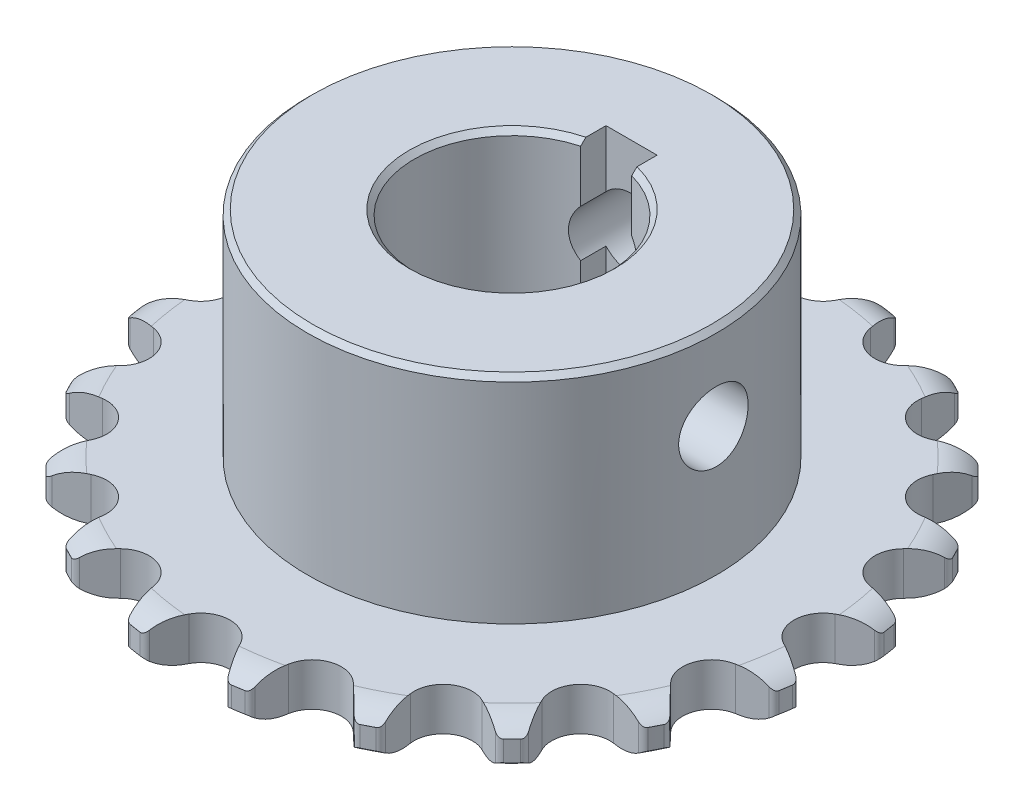
SolidWorks part; units mm, degrees
ref_plane "Alzado" through (0, 0, 0) normal (0, 0, 1) x (1, 0, 0)
ref_plane "Planta" through (0, 0, 0) normal (0, 1, 0) x (1, 0, 0)
ref_plane "Vista lateral" through (0, 0, 0) normal (1, 0, 0) x (0, 0, -1)
sketch "Croquis1" plane through (0, 0, 0) normal (0, 1, 0) x (1, 0, 0)
  circle A0 centre (0, 0) radius 9.55
  circle A1 centre (0, 0) radius 20
  dimension "D1" = 40
  dimension "D2" = 19.1
extrude "Saliente-Extruir1" add sketch "Croquis1" along normal blind 25.2
sketch "Croquis2" plane through (0, 25.2, 0) normal (0, 1, 0) x (1, 0, 0)
  line L0 (0, 11.7) -> (0, 20) construction
  line L1 (-2.5, 11.7) -> (2.5, 11.7)
  line L2 (-2.5, 11.7) -> (-2.5, 0)
  line L3 (-2.5, 0) -> (2.5, 0)
  line L4 (2.5, 11.7) -> (2.5, 0)
  circle A1 centre (0, 0) radius 20 construction
  point P4 (0, 11.7)
  point P13 (0, 0)
  dimension "D1" = 8.3
  dimension "D2" = 5
extrude "Cortar-Extruir1" cut sketch "Croquis2" against normal through all
sketch "Croquis4" plane through (0, 0, 0) normal (0, 0, 1) x (1, 0, 0)
  line L0 (0, 17.3) -> (0, 20.7) construction
  line L2 (9.55, 25.2) -> (-9.55, 25.2) construction
  circle A0 centre (0, 17.3) radius 3.4
  dimension "D2" = 6.8
  dimension "D1" = 4.5
extrude "Cortar-Extruir2" cut sketch "Croquis4" against normal through all
sketch "Croquis5" plane through (0, 0, 0) normal (1, 0, 0) x (0, 0, -1)
  line L0 (0, 16.8) -> (0, 20.2) construction
  line L2 (20, 25.2) -> (-20, 25.2) construction
  circle A0 centre (0, 16.8) radius 3.4
  dimension "D2" = 6.8
  dimension "D1" = 5
extrude "Cortar-Extruir3" cut sketch "Croquis5" along normal through all
sketch "Croquis6" plane through (0, 0, 0) normal (0, -1, 0) x (1, 0, 0)
  circle A0 centre (0, 0) radius 32.25
  circle A2 centre (0, 0) radius 20 construction
  circle A4 centre (0, 0) radius 18
  dimension "D1" = 64.5
  dimension "D2" = 2
extrude "Saliente-Extruir2" add sketch "Croquis6" against normal blind 4.2
sketch "Croquis11" plane through (0, 4.2, 0) normal (0, 1, 0) x (1, 0, 0)
  line L0 (0, 30.45) -> (0, 27.6) construction
  line L1 (2.5, 11.7) -> (-2.5, 11.7) construction
  circle A0 centre (0, 30.45) radius 2.85
  circle A1 centre (9.4096, 28.9597) radius 2.85
  circle A2 centre (17.8981, 24.6346) radius 2.85
  circle A3 centre (24.6346, 17.8981) radius 2.85
  circle A4 centre (28.9597, 9.4096) radius 2.85
  circle A5 centre (30.45, 0) radius 2.85
  circle A6 centre (28.9597, -9.4096) radius 2.85
  circle A7 centre (24.6346, -17.8981) radius 2.85
  circle A8 centre (17.8981, -24.6346) radius 2.85
  circle A9 centre (9.4096, -28.9597) radius 2.85
  circle A10 centre (0, -30.45) radius 2.85
  circle A11 centre (-9.4096, -28.9597) radius 2.85
  circle A12 centre (-17.8981, -24.6346) radius 2.85
  circle A13 centre (-24.6346, -17.8981) radius 2.85
  circle A14 centre (-28.9597, -9.4096) radius 2.85
  circle A15 centre (-30.45, 0) radius 2.85
  circle A16 centre (-28.9597, 9.4096) radius 2.85
  circle A17 centre (-24.6346, 17.8981) radius 2.85
  circle A18 centre (-17.8981, 24.6346) radius 2.85
  circle A19 centre (-9.4096, 28.9597) radius 2.85
  circle A20 centre (0, 0) radius 20 construction
  dimension "D1" = 5.7
  dimension "D2" = 15.9
  dimension "D4" = 9.4096
  dimension "D5" = 17.8981
  dimension "D6" = 24.6346
  dimension "D7" = 28.9597
  dimension "D8" = 30.45
  dimension "D9" = 17.8981
  dimension "D10" = 24.6346
  dimension "D11" = 28.9597
  dimension "D12" = 30.45
  dimension "D13" = 9.4096
  dimension "D3" = 9.4096
  dimension "D14" = 17.8981
  dimension "D15" = 24.6346
  dimension "D16" = 28.9597
  dimension "D17" = 9.4096
  dimension "D18" = 17.8981
  dimension "D19" = 24.6346
  dimension "D20" = 28.9597
  dimension "D21" = 30.45
  dimension "D22" = 30.45
  dimension "D23" = 30.45
  dimension "D24" = 30.45
extrude "Cortar-Extruir9" cut sketch "Croquis11" against normal through all
sketch "Croquis12" plane through (0, 4.2, 0) normal (0, 1, 0) x (1, 0, 0)
  line L0 (2.5142, 29.1078) -> (4.055, 31.9941)
  line L1 (6.0304, 31.6812) -> (6.6037, 28.4603)
  line L2 (2.2726, 32.1698) -> (3.555, 32.8941)
  line L3 (3.555, 32.8941) -> (4.055, 31.9941)
  line L4 (6.0304, 31.6812) -> (6.5304, 32.4295)
  line L5 (6.5304, 32.4295) -> (7.7797, 31.2976)
  line L6 (11.3859, 26.9062) -> (13.7433, 29.1751)
  line L7 (13.5458, 30.1855) -> (13.7433, 29.1751)
  line L8 (12.1024, 29.8931) -> (13.5458, 30.1855)
  line L9 (15.5253, 28.2671) -> (15.0752, 25.0267)
  line L10 (16.232, 28.8243) -> (17.0704, 27.3617)
  line L11 (15.5253, 28.2671) -> (16.232, 28.8243)
  line L12 (19.1431, 22.0709) -> (22.0862, 23.5003)
  line L13 (22.2107, 24.5223) -> (22.0862, 23.5003)
  line L14 (20.7475, 24.6901) -> (22.2107, 24.5223)
  line L15 (23.5004, 22.086) -> (22.071, 19.1433)
  line L16 (24.3448, 22.3976) -> (24.6901, 20.7475)
  line L17 (23.5004, 22.086) -> (24.3448, 22.3976)
  line L18 (25.0265, 15.0751) -> (28.2672, 15.5251)
  line L19 (28.7014, 16.4586) -> (28.2672, 15.5251)
  line L20 (27.3617, 17.0704) -> (28.7014, 16.4586)
  line L21 (29.1752, 13.743) -> (26.9064, 11.386)
  line L22 (30.0745, 13.7784) -> (29.8931, 12.1024)
  line L23 (29.1752, 13.743) -> (30.0745, 13.7784)
  line L24 (28.4601, 6.6037) -> (31.6812, 6.0302)
  line L25 (32.3827, 6.7838) -> (31.6812, 6.0302)
  line L26 (31.2976, 7.7797) -> (32.3827, 6.7838)
  line L27 (31.9941, 4.0548) -> (29.108, 2.5142)
  line L28 (32.8603, 3.8105) -> (32.1698, 2.2726)
  line L29 (31.9941, 4.0548) -> (32.8603, 3.8105)
  line L30 (29.1078, -2.5142) -> (31.9941, -4.055)
  line L31 (32.8941, -3.555) -> (31.9941, -4.055)
  line L32 (32.1698, -2.2726) -> (32.8941, -3.555)
  line L33 (31.6812, -6.0304) -> (28.4603, -6.6037)
  line L34 (32.4295, -6.5304) -> (31.2976, -7.7797)
  line L35 (31.6812, -6.0304) -> (32.4295, -6.5304)
  line L36 (26.9062, -11.3859) -> (29.1751, -13.7433)
  line L37 (30.1855, -13.5458) -> (29.1751, -13.7433)
  line L38 (29.8931, -12.1024) -> (30.1855, -13.5458)
  line L39 (28.2671, -15.5253) -> (25.0267, -15.0752)
  line L40 (28.8243, -16.232) -> (27.3617, -17.0704)
  line L41 (28.2671, -15.5253) -> (28.8243, -16.232)
  line L42 (22.0709, -19.1431) -> (23.5003, -22.0862)
  line L43 (24.5223, -22.2107) -> (23.5003, -22.0862)
  line L44 (24.6901, -20.7475) -> (24.5223, -22.2107)
  line L45 (22.086, -23.5004) -> (19.1433, -22.071)
  line L46 (22.3976, -24.3448) -> (20.7475, -24.6901)
  line L47 (22.086, -23.5004) -> (22.3976, -24.3448)
  line L48 (15.0751, -25.0265) -> (15.5251, -28.2672)
  line L49 (16.4586, -28.7014) -> (15.5251, -28.2672)
  line L50 (17.0704, -27.3617) -> (16.4586, -28.7014)
  line L51 (13.743, -29.1752) -> (11.386, -26.9064)
  line L52 (13.7784, -30.0745) -> (12.1024, -29.8931)
  line L53 (13.743, -29.1752) -> (13.7784, -30.0745)
  line L54 (6.6037, -28.4601) -> (6.0302, -31.6812)
  line L55 (6.7838, -32.3827) -> (6.0302, -31.6812)
  line L56 (7.7797, -31.2976) -> (6.7838, -32.3827)
  line L57 (4.0548, -31.9941) -> (2.5142, -29.108)
  line L58 (3.8105, -32.8603) -> (2.2726, -32.1698)
  line L59 (4.0548, -31.9941) -> (3.8105, -32.8603)
  line L60 (-2.5142, -29.1078) -> (-4.055, -31.9941)
  line L61 (-3.555, -32.8941) -> (-4.055, -31.9941)
  line L62 (-2.2726, -32.1698) -> (-3.555, -32.8941)
  line L63 (-6.0304, -31.6812) -> (-6.6037, -28.4603)
  line L64 (-6.5304, -32.4295) -> (-7.7797, -31.2976)
  line L65 (-6.0304, -31.6812) -> (-6.5304, -32.4295)
  line L66 (-11.3859, -26.9062) -> (-13.7433, -29.1751)
  line L67 (-13.5458, -30.1855) -> (-13.7433, -29.1751)
  line L68 (-12.1024, -29.8931) -> (-13.5458, -30.1855)
  line L69 (-15.5253, -28.2671) -> (-15.0752, -25.0267)
  line L70 (-16.232, -28.8243) -> (-17.0704, -27.3617)
  line L71 (-15.5253, -28.2671) -> (-16.232, -28.8243)
  line L72 (-19.1431, -22.0709) -> (-22.0862, -23.5003)
  line L73 (-22.2107, -24.5223) -> (-22.0862, -23.5003)
  line L74 (-20.7475, -24.6901) -> (-22.2107, -24.5223)
  line L75 (-23.5004, -22.086) -> (-22.071, -19.1433)
  line L76 (-24.3448, -22.3976) -> (-24.6901, -20.7475)
  line L77 (-23.5004, -22.086) -> (-24.3448, -22.3976)
  line L78 (-25.0265, -15.0751) -> (-28.2672, -15.5251)
  line L79 (-28.7014, -16.4586) -> (-28.2672, -15.5251)
  line L80 (-27.3617, -17.0704) -> (-28.7014, -16.4586)
  line L81 (-29.1752, -13.743) -> (-26.9064, -11.386)
  line L82 (-30.0745, -13.7784) -> (-29.8931, -12.1024)
  line L83 (-29.1752, -13.743) -> (-30.0745, -13.7784)
  line L84 (-28.4601, -6.6037) -> (-31.6812, -6.0302)
  line L85 (-32.3827, -6.7838) -> (-31.6812, -6.0302)
  line L86 (-31.2976, -7.7797) -> (-32.3827, -6.7838)
  line L87 (-31.9941, -4.0548) -> (-29.108, -2.5142)
  line L88 (-32.8603, -3.8105) -> (-32.1698, -2.2726)
  line L89 (-31.9941, -4.0548) -> (-32.8603, -3.8105)
  line L90 (-29.1078, 2.5142) -> (-31.9941, 4.055)
  line L91 (-32.8941, 3.555) -> (-31.9941, 4.055)
  line L92 (-32.1698, 2.2726) -> (-32.8941, 3.555)
  line L93 (-31.6812, 6.0304) -> (-28.4603, 6.6037)
  line L94 (-32.4295, 6.5304) -> (-31.2976, 7.7797)
  line L95 (-31.6812, 6.0304) -> (-32.4295, 6.5304)
  line L96 (-26.9062, 11.3859) -> (-29.1751, 13.7433)
  line L97 (-30.1855, 13.5458) -> (-29.1751, 13.7433)
  line L98 (-29.8931, 12.1024) -> (-30.1855, 13.5458)
  line L99 (-28.2671, 15.5253) -> (-25.0267, 15.0752)
  line L100 (-28.8243, 16.232) -> (-27.3617, 17.0704)
  line L101 (-28.2671, 15.5253) -> (-28.8243, 16.232)
  line L102 (-22.0709, 19.1431) -> (-23.5003, 22.0862)
  line L103 (-24.5223, 22.2107) -> (-23.5003, 22.0862)
  line L104 (-24.6901, 20.7475) -> (-24.5223, 22.2107)
  line L105 (-22.086, 23.5004) -> (-19.1433, 22.071)
  line L106 (-22.3976, 24.3448) -> (-20.7475, 24.6901)
  line L107 (-22.086, 23.5004) -> (-22.3976, 24.3448)
  line L108 (-15.0751, 25.0265) -> (-15.5251, 28.2672)
  line L109 (-16.4586, 28.7014) -> (-15.5251, 28.2672)
  line L110 (-17.0704, 27.3617) -> (-16.4586, 28.7014)
  line L111 (-13.743, 29.1752) -> (-11.386, 26.9064)
  line L112 (-13.7784, 30.0745) -> (-12.1024, 29.8931)
  line L113 (-13.743, 29.1752) -> (-13.7784, 30.0745)
  line L114 (-6.6037, 28.4601) -> (-6.0302, 31.6812)
  line L115 (-6.7838, 32.3827) -> (-6.0302, 31.6812)
  line L116 (-7.7797, 31.2976) -> (-6.7838, 32.3827)
  line L117 (-4.0548, 31.9941) -> (-2.5142, 29.108)
  line L118 (-3.8105, 32.8603) -> (-2.2726, 32.1698)
  line L119 (-4.0548, 31.9941) -> (-3.8105, 32.8603)
  arc A0 (7.7797, 31.2976) -> (6.6037, 28.4603) centre (9.4096, 28.9597) ccw
  arc A1 (2.5142, 29.1078) -> (2.2726, 32.1698) centre (0, 30.45) ccw
  circle A2 centre (0, 0) radius 32.25 construction
  arc A5 (11.3859, 26.9062) -> (12.1024, 29.8931) centre (9.4096, 28.9597) ccw
  arc A6 (17.0704, 27.3617) -> (15.0752, 25.0267) centre (17.8981, 24.6346) ccw
  arc A7 (19.1431, 22.0709) -> (20.7475, 24.6901) centre (17.8981, 24.6346) ccw
  arc A8 (24.6901, 20.7475) -> (22.071, 19.1433) centre (24.6346, 17.8981) ccw
  arc A9 (25.0265, 15.0751) -> (27.3617, 17.0704) centre (24.6346, 17.8981) ccw
  arc A10 (29.8931, 12.1024) -> (26.9064, 11.386) centre (28.9597, 9.4096) ccw
  arc A11 (28.4601, 6.6037) -> (31.2976, 7.7797) centre (28.9597, 9.4096) ccw
  arc A12 (32.1698, 2.2726) -> (29.108, 2.5142) centre (30.45, 0) ccw
  arc A13 (29.1078, -2.5142) -> (32.1698, -2.2726) centre (30.45, 0) ccw
  arc A14 (31.2976, -7.7797) -> (28.4603, -6.6037) centre (28.9597, -9.4096) ccw
  arc A15 (26.9062, -11.3859) -> (29.8931, -12.1024) centre (28.9597, -9.4096) ccw
  arc A16 (27.3617, -17.0704) -> (25.0267, -15.0752) centre (24.6346, -17.8981) ccw
  arc A17 (22.0709, -19.1431) -> (24.6901, -20.7475) centre (24.6346, -17.8981) ccw
  arc A18 (20.7475, -24.6901) -> (19.1433, -22.071) centre (17.8981, -24.6346) ccw
  arc A19 (15.0751, -25.0265) -> (17.0704, -27.3617) centre (17.8981, -24.6346) ccw
  arc A20 (12.1024, -29.8931) -> (11.386, -26.9064) centre (9.4096, -28.9597) ccw
  arc A21 (6.6037, -28.4601) -> (7.7797, -31.2976) centre (9.4096, -28.9597) ccw
  arc A22 (2.2726, -32.1698) -> (2.5142, -29.108) centre (0, -30.45) ccw
  arc A23 (-2.5142, -29.1078) -> (-2.2726, -32.1698) centre (0, -30.45) ccw
  arc A24 (-7.7797, -31.2976) -> (-6.6037, -28.4603) centre (-9.4096, -28.9597) ccw
  arc A25 (-11.3859, -26.9062) -> (-12.1024, -29.8931) centre (-9.4096, -28.9597) ccw
  arc A26 (-17.0704, -27.3617) -> (-15.0752, -25.0267) centre (-17.8981, -24.6346) ccw
  arc A27 (-19.1431, -22.0709) -> (-20.7475, -24.6901) centre (-17.8981, -24.6346) ccw
  arc A28 (-24.6901, -20.7475) -> (-22.071, -19.1433) centre (-24.6346, -17.8981) ccw
  arc A29 (-25.0265, -15.0751) -> (-27.3617, -17.0704) centre (-24.6346, -17.8981) ccw
  arc A30 (-29.8931, -12.1024) -> (-26.9064, -11.386) centre (-28.9597, -9.4096) ccw
  arc A31 (-28.4601, -6.6037) -> (-31.2976, -7.7797) centre (-28.9597, -9.4096) ccw
  arc A32 (-32.1698, -2.2726) -> (-29.108, -2.5142) centre (-30.45, 0) ccw
  arc A33 (-29.1078, 2.5142) -> (-32.1698, 2.2726) centre (-30.45, 0) ccw
  arc A34 (-31.2976, 7.7797) -> (-28.4603, 6.6037) centre (-28.9597, 9.4096) ccw
  arc A35 (-26.9062, 11.3859) -> (-29.8931, 12.1024) centre (-28.9597, 9.4096) ccw
  arc A36 (-27.3617, 17.0704) -> (-25.0267, 15.0752) centre (-24.6346, 17.8981) ccw
  arc A37 (-22.0709, 19.1431) -> (-24.6901, 20.7475) centre (-24.6346, 17.8981) ccw
  arc A38 (-20.7475, 24.6901) -> (-19.1433, 22.071) centre (-17.8981, 24.6346) ccw
  arc A39 (-15.0751, 25.0265) -> (-17.0704, 27.3617) centre (-17.8981, 24.6346) ccw
  arc A40 (-12.1024, 29.8931) -> (-11.386, 26.9064) centre (-9.4096, 28.9597) ccw
  arc A41 (-6.6037, 28.4601) -> (-7.7797, 31.2976) centre (-9.4096, 28.9597) ccw
  arc A42 (-2.2726, 32.1698) -> (-2.5142, 29.108) centre (0, 30.45) ccw
  point P30 (5.045, 31.8529)
  dimension "D1" = 0.5
  dimension "D4" = 0.5
  dimension "D5" = 1
  dimension "D6" = 2
extrude "Cortar-Extruir10" cut sketch "Croquis12" against normal through all
fillet "Redondeo4" radius 0.6 40 edges at (15.5251, 2.1, 28.2672) (23.5003, 2.1, 22.0862) (28.2671, 2.1, 15.5253) (29.1751, 2.1, 13.7433) (31.6812, 2.1, 6.0304) (31.9941, 2.1, 4.055) (31.9941, 2.1, -4.0548) (31.6812, 2.1, -6.0302) (29.1752, 2.1, -13.743) (28.2672, 2.1, -15.5251) (23.5004, 2.1, -22.086) (22.0862, 2.1, -23.5003) (15.5253, 2.1, -28.2671) (13.7433, 2.1, -29.1751) (6.0304, 2.1, -31.6812) (4.055, 2.1, -31.9941) (-4.0548, 2.1, -31.9941) (-6.0302, 2.1, -31.6812) (-13.743, 2.1, -29.1752) (-15.5251, 2.1, -28.2672) (-22.086, 2.1, -23.5004) (-23.5003, 2.1, -22.0862) (-28.2671, 2.1, -15.5253) (-29.1751, 2.1, -13.7433) (-31.6812, 2.1, -6.0304) (-31.9941, 2.1, -4.055) (-31.9941, 2.1, 4.0548) (-31.6812, 2.1, 6.0302) (-29.1752, 2.1, 13.743) (-28.2672, 2.1, 15.5251) (-23.5004, 2.1, 22.086) (-22.0862, 2.1, 23.5003) (-15.5253, 2.1, 28.2671) (-13.7433, 2.1, 29.1751) (-6.0304, 2.1, 31.6812) (-4.055, 2.1, 31.9941) (4.0548, 2.1, 31.9941) (6.0302, 2.1, 31.6812) (13.743, 2.1, 29.1752) (22.086, 2.1, 23.5004)
ref_plane "Plano1" through (5.0449, 4.2, 31.853) normal (-0.9877, 0, 0.1564) x (0.1564, 0, 0.9877)
sketch "Croquis16" plane through (5.0449, 4.2, 31.853) normal (-0.9877, 0, 0.1564) x (0.1564, 0, 0.9877)
  line L0 (-32.25, -4.2) -> (-32.25, 21) construction
  line L2 (-0.0052, -1.1) -> (0.1948, -1.1)
  line L3 (0.1948, 0) -> (-2.7602, 0)
  line L4 (-0.4089, 0) -> (-3.1071, 0) construction
  line L5 (-0.0052, -2.1) -> (-4.2698, -2.1) construction
  line L6 (-0.0052, 0) -> (-0.0052, -4.2) construction
  line L7 (-2.3184, 0) -> (-5.1731, 0) construction
  line L8 (0.1948, -1.1) -> (0.1948, 0)
  line L9 (0.1948, -3.1) -> (0.1948, -4.2)
  line L10 (-0.0052, -3.1) -> (0.1948, -3.1)
  line L11 (0.1948, -4.2) -> (-2.7602, -4.2)
  arc A0 (-0.0052, -1.1) -> (-2.7602, 0) centre (-2.7602, -4) ccw
  arc A1 (-0.0052, -3.1) -> (-2.7602, -4.2) centre (-2.7602, -0.2) cw
  dimension "D1" = 4
  dimension "D2" = 1
  dimension "D3" = 0.2
revolve "Cortar-Revolución3" cut sketch "Croquis16" angle 360 about L0
chamfer "Chaflán3" distance 0.5 angle 45 3 edges at (0, 25.2, 9.55) (0, 0, 9.55) (0, 25.2, 20)
